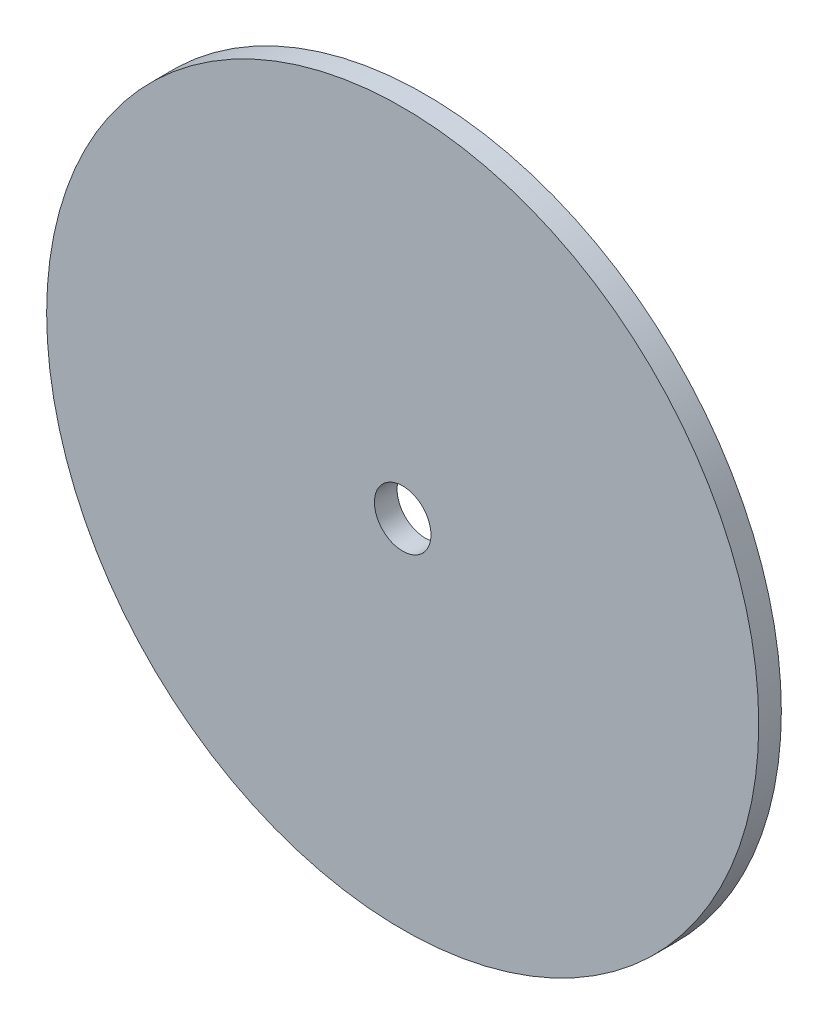
SolidWorks part; units mm, degrees
ref_plane "Front Plane" through (0, 0, 0) normal (0, 0, 1) x (1, 0, 0)
ref_plane "Top Plane" through (0, 0, 0) normal (0, 1, 0) x (1, 0, 0)
ref_plane "Right Plane" through (0, 0, 0) normal (1, 0, 0) x (0, 0, -1)
sketch "Sketch1" plane through (0, 0, 0) normal (0, 0, 1) x (1, 0, 0)
  circle A0 centre (0, 0) radius 100
  circle A1 centre (0, 0) radius 7.9375
  point P4 (0, 0)
  dimension "D1" = 200
  dimension "D2" = 15.875
extrude "Boss-Extrude1" add sketch "Sketch1" along normal blind 6.35
